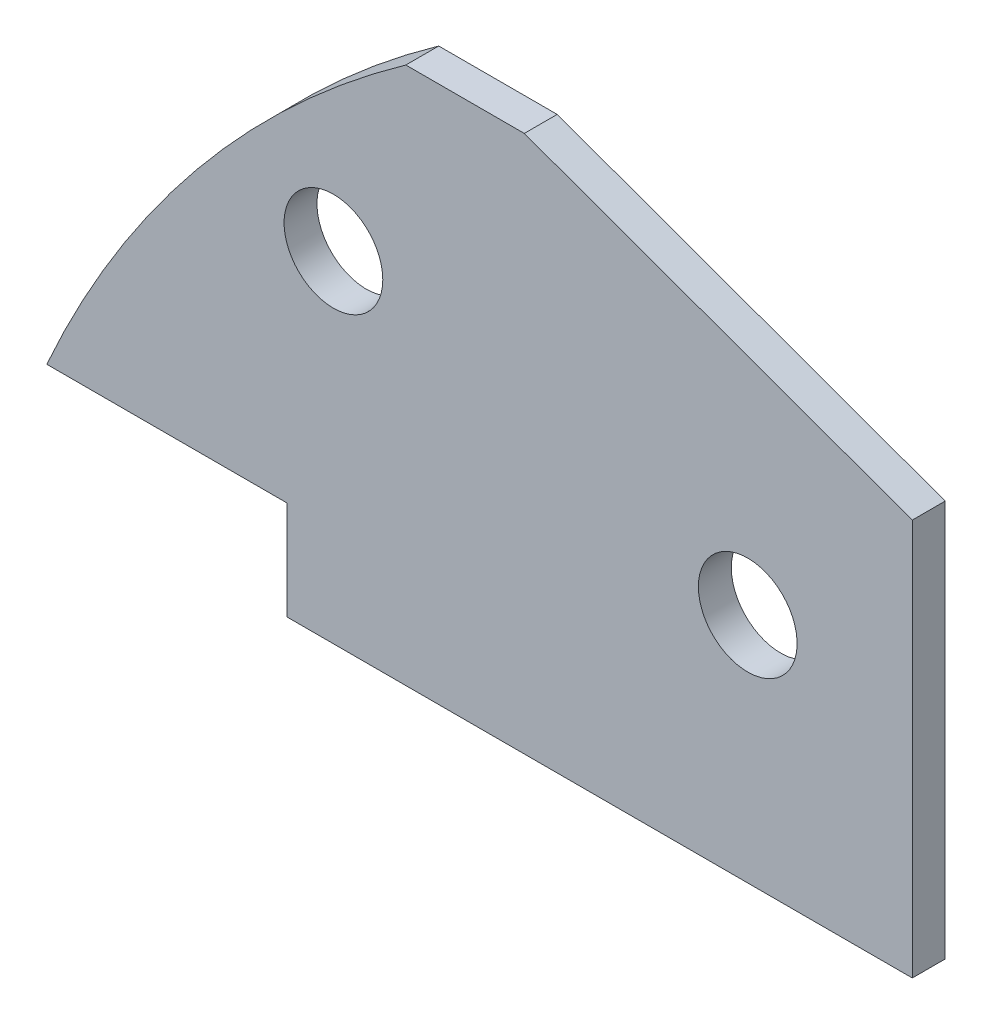
SolidWorks part; units mm, degrees
ref_plane "Front Plane" through (0, 0, 0) normal (0, 0, 1) x (1, 0, 0)
ref_plane "Top Plane" through (0, 0, 0) normal (0, 1, 0) x (1, 0, 0)
ref_plane "Right Plane" through (0, 0, 0) normal (1, 0, 0) x (0, 0, -1)
sketch "Sketch1" plane through (0, 0, 0) normal (0, 0, 1) x (1, 0, 0)
  line L2 (11, 25.5) -> (-11, 25.5)
  line L3 (-11, 25.5) -> (-22.79, 29.7803)
  line L4 (11, 25.5) -> (22.79, 29.7803)
  arc A0 (-22.79, 29.7803) -> (22.79, 29.7803) centre (0, 0) ccw
  arc A1 (-22.79, 29.7803) -> (22.79, 29.7803) centre (0, 0) ccw
  dimension "D2" = 37.5
extrude "Boss-Extrude1" add sketch "Sketch1" along normal blind 3 contours L3 A0 L4 L2
sketch "Sketch2" plane through (0, 0, 3) normal (0, 0, 1) x (1, 0, 0)
  line L0 (0, 0) -> (-25.8, 0) construction
  line L2 (0, 0) -> (0, 15.281) construction
  circle A4 centre (-25.4, 10.4969) radius 1.5
  circle A5 centre (-25.4, -10.4931) radius 1.5
  circle A6 centre (25.4, -10.4931) radius 1.5
  circle A7 centre (25.4, 10.4969) radius 1.5
  point P6 (-25.8, 0)
  dimension "D1" = 25.8
  dimension "D2" = 20.99
extrude "Cut-Extrude3" cut sketch "Sketch2" against normal blind 3
sketch "Sketch3" plane through (0, 0, 3) normal (0, 0, 1) x (1, 0, 0)
  line L1 (-30.76, 21.4493) -> (-30.76, -21.4493)
  line L3 (30.76, 21.4493) -> (30.76, -21.4493)
  arc A0 (-22.79, 29.7803) -> (22.79, 29.7803) centre (0, 0) ccw construction
  arc A1 (-30.76, 21.4493) -> (-30.76, -21.4493) centre (0, 0) ccw
  arc A2 (30.76, 21.4493) -> (30.76, -21.4493) centre (0, 0) cw
  point P10 (-30.76, 0)
extrude "Cut-Extrude4" cut sketch "Sketch3" against normal blind 10
sketch "Sketch4" plane through (0, 0, 3) normal (0, 0, 1) x (1, 0, 0)
  line L0 (-30.76, 21.4493) -> (-30.76, 16.4493) construction
  line L1 (-30.76, -21.4493) -> (-30.76, 21.4493) construction
  line L2 (30.76, 21.4493) -> (30.76, 16.4493) construction
  line L3 (30.76, 21.4493) -> (30.76, -21.4493) construction
  line L4 (-30.76, -21.4493) -> (-30.76, -16.4493) construction
  line L5 (30.76, -21.4493) -> (30.76, -16.4493) construction
  line L6 (-30.76, -16.4493) -> (-33.6997, -16.4493)
  line L7 (-30.76, 16.4493) -> (-33.6997, 16.4493)
  line L8 (30.76, 16.4493) -> (33.6997, 16.4493)
  line L9 (30.76, -16.4493) -> (33.6997, -16.4493)
  line L10 (30.76, -21.4493) -> (30.76, -16.4493)
  line L11 (30.76, 21.4493) -> (30.76, 16.4493)
  line L12 (-30.76, 16.4493) -> (-30.76, 21.4493)
  line L13 (-30.76, -21.4493) -> (-30.76, -16.4493)
  arc A0 (-33.6997, -16.4493) -> (33.6997, -16.4493) centre (0, 0) ccw
  arc A1 (-30.76, 21.4493) -> (-33.6997, 16.4493) centre (0, 0) ccw
  arc A2 (33.6997, 16.4493) -> (30.76, 21.4493) centre (0, 0) ccw
  line M2 (30.76, -21.4493) -> (30.76, 21.4493)
  line M8 (-30.76, 21.4493) -> (-30.76, -21.4493)
  dimension "D1" = 5
  dimension "D2" = 5
extrude "Boss-Extrude2" add sketch "Sketch4" against normal blind 3 contours L6 A0 M8 | A1 L7 M8 | L8 A2 M2 | A0 L9 M2
sketch "Sketch5" plane through (0, 0, 3) normal (0, 0, 1) x (1, 0, 0)
  line L0 (-30.76, 16.4493) -> (-30.2, 16.4493) construction
  line L1 (-30.76, -16.4493) -> (-30.2, -16.4493) construction
  line L2 (0, 0) -> (0, -3.3934) construction
  line L3 (-30.2, -16.4493) -> (-30.76, -16.4493)
  line L4 (-30.2, -16.4493) -> (-30.2, 16.4493)
  line L5 (-30.2, 16.4493) -> (-30.76, 16.4493)
  line L6 (-30.76, -16.4493) -> (-30.76, 16.4493)
  line L7 (30.76, -16.4493) -> (30.2, -16.4493) construction
  line L8 (30.76, 16.4493) -> (30.2, 16.4493) construction
  line L9 (30.76, -16.4493) -> (30.76, 16.4493)
  line L10 (30.2, 16.4493) -> (30.76, 16.4493)
  line L11 (30.2, -16.4493) -> (30.2, 16.4493)
  line L12 (30.2, -16.4493) -> (30.76, -16.4493)
  dimension "D2" = 0.56
extrude "Cut-Extrude5" cut sketch "Sketch5" against normal blind 3
sketch "Sketch6" plane through (0, 0, 3) normal (0, 0, 1) x (1, 0, 0)
  line L1 (-30.2, 16.4493) -> (-30, 16.4493)
  line L2 (-30.2, 16.4493) -> (-30.2, -16.4493)
  line L3 (-30.2, -16.4493) -> (-30, -16.4493)
  line L4 (-30, 16.4493) -> (-30, -16.4493)
  line L5 (30, 16.4493) -> (30, -16.4493)
  line L6 (30.2, -16.4493) -> (30, -16.4493)
  line L7 (30.2, 16.4493) -> (30.2, -16.4493)
  line L8 (30.2, 16.4493) -> (30, 16.4493)
  dimension "D1" = 0.2
extrude "Cut-Extrude6" cut sketch "Sketch6" against normal blind 3
sketch "Sketch7" plane through (0, 0, 3) normal (0, 0, 1) x (1, 0, 0)
  line L0 (0, -37.5) -> (0, -5.6) construction
  line L1 (0, -21.55) -> (-21.15, -21.55) construction
  line L2 (-21.15, -21.55) -> (-19.15, -21.55) construction
  arc A0 (-33.6997, -16.4493) -> (33.6997, -16.4493) centre (0, 0) ccw construction
  circle A1 centre (-19.15, -21.55) radius 2
  circle A2 centre (19.15, -21.55) radius 2
  dimension "D1" = 31.9
  dimension "D2" = 21.15
  dimension "D3" = 2
extrude "Cut-Extrude8" cut sketch "Sketch7" against normal blind 3 contours A1 | A2
sketch "Sketch8" plane through (0, 0, 3) normal (0, 0, 1) x (1, 0, 0)
  line L2 (-33.6997, 16.4493) -> (-37.2997, 16.4493)
  line L3 (33.6997, 16.4493) -> (37.2997, 16.4493)
  line L4 (-22.79, 29.7803) -> (-26.39, 29.7803)
  line L5 (22.79, 29.7803) -> (26.39, 29.7803)
  line L6 (0, 0) -> (0, 7.7073) construction
  arc A0 (-37.2997, 16.4493) -> (-26.39, 29.7803) centre (-7.6125, 3.2837) cw
  arc A1 (37.2997, 16.4493) -> (26.39, 29.7803) centre (7.6125, 3.2837) ccw
  arc A7 (-33.6997, 16.4493) -> (-22.79, 29.7803) centre (0, 0) cw
  arc A8 (22.79, 29.7803) -> (33.6997, 16.4493) centre (0, 0) cw
  dimension "D4" = 3.6
extrude "Boss-Extrude3" add sketch "Sketch8" against normal blind 3
sketch "Sketch9" plane through (0, 0, 3) normal (0, 0, 1) x (1, 0, 0)
  line L0 (0, 0) -> (0, 9.4958) construction
  line L1 (0, -37.5) -> (0, -37.2) construction
  line L2 (4.7339, -37.2) -> (-4.7339, -37.2)
  arc A0 (-33.6997, -16.4493) -> (33.6997, -16.4493) centre (0, 0) ccw construction
  arc A1 (-4.7339, -37.2) -> (4.7339, -37.2) centre (0, 0) ccw
  point P15 (0, -37.2)
  dimension "D1" = 0.3
extrude "Cut-Extrude9" cut sketch "Sketch9" against normal blind 3
sketch "Sketch10" plane through (0, 0, 3) normal (0, 0, 1) x (1, 0, 0)
  line L0 (-33.6997, -16.4493) -> (-37.2997, -16.4493)
  line L1 (-33.6997, -16.4493) -> (-37.2997, -16.4493) construction
  line L2 (0, 0) -> (0, 6.5031) construction
  line L3 (33.6997, -16.4493) -> (37.2997, -16.4493)
  line L4 (-4.7339, -37.2) -> (4.7339, -37.2)
  arc A0 (-37.2997, -16.4493) -> (37.2997, -16.4493) centre (0, 6.1588) ccw
  arc A1 (-33.6997, -16.4493) -> (-4.7339, -37.2) centre (0, 0) ccw
  arc A2 (33.6997, -16.4493) -> (4.7339, -37.2) centre (0, 0) cw
extrude "Boss-Extrude5" add sketch "Sketch10" against normal blind 3
sketch "Sketch11" plane through (0, 0, 3) normal (0, 0, 1) x (1, 0, 0)
  line L0 (-30, 16.4493) -> (-30, 13.4493)
  line L1 (-30, -16.4493) -> (-30, 16.4493) construction
  line L2 (-30, 13.4493) -> (30, 13.4493)
  line L3 (30, 16.4493) -> (30, -16.4493) construction
  line L4 (30, 13.4493) -> (30, 16.4493)
  line L5 (30, 16.4493) -> (37.2997, 16.4493)
  line L6 (-30, 16.4493) -> (-37.2997, 16.4493)
  line L7 (-26.39, 29.7803) -> (-22.79, 29.7803)
  line L8 (-22.79, 29.7803) -> (-11, 25.5)
  line L9 (-11, 25.5) -> (11, 25.5)
  line L10 (11, 25.5) -> (22.79, 29.7803)
  line L11 (22.79, 29.7803) -> (26.39, 29.7803)
  arc A0 (-37.2997, 16.4493) -> (-26.39, 29.7803) centre (-7.6125, 3.2837) cw
  arc A1 (37.2997, 16.4493) -> (26.39, 29.7803) centre (7.6125, 3.2837) ccw
  dimension "D1" = 3
extrude "Cut-Extrude10" cut sketch "Sketch11" against normal blind 2
sketch "Sketch12" plane through (0, 0, 3) normal (0, 0, 1) x (1, 0, 0)
  line L0 (-30, 13.4493) -> (-30, -16.4493)
  line L1 (-30, -16.4493) -> (-37.2997, -16.4493)
  line L2 (-30, 13.4493) -> (30, 13.4493)
  line L3 (30, 13.4493) -> (30, -16.4493)
  line L4 (30, -16.4493) -> (37.2997, -16.4493)
  arc A0 (-37.2997, -16.4493) -> (37.2997, -16.4493) centre (0, 6.1588) ccw
extrude "Cut-Extrude11" cut sketch "Sketch12" against normal blind 3
sketch "Sketch13" plane through (0, 0, 1) normal (0, 0, 1) x (1, 0, 0)
  line L0 (-24.59, 29.7803) -> (-24.59, 23.7803) construction
  line L1 (-22.79, 29.7803) -> (-26.39, 29.7803) construction
  line L2 (-24.59, 23.7803) -> (-28.59, 23.7803) construction
  circle A0 centre (-28.59, 23.7803) radius 1.5
  circle A1 centre (28.59, 23.7803) radius 1.5
  dimension "D3" = 3
  dimension "D1" = 6
  dimension "D2" = 4
extrude "Cut-Extrude12" cut sketch "Sketch13" against normal blind 1
sketch "Sketch14" plane through (0, 0, 0) normal (0, 0, -1) x (-1, 0, 0)
  line L0 (11, 25.5) -> (11, 13.4493)
  line L1 (-30, 13.4493) -> (30, 13.4493) construction
  line L2 (11, 13.4493) -> (-37.9211, 13.4493)
  line L3 (-37.9211, 13.4493) -> (-37.9211, 32.1404)
  line L4 (-37.9211, 32.1404) -> (-13.4606, 32.1404)
  line L5 (-13.4606, 32.1404) -> (-11, 25.5)
  line L6 (-11, 25.5) -> (11, 25.5)
extrude "Cut-Extrude13" cut sketch "Sketch14" against normal blind 1
sketch "Sketch16" plane through (0, 0, 0) normal (0, 0, -1) x (-1, 0, 0)
  line L0 (11, 25.5) -> (16, 25.5) construction
  line L1 (16, 25.5) -> (16, 20.5) construction
  circle A0 centre (16, 20.5) radius 1.5
  dimension "D1" = 5
  dimension "D2" = 5
extrude "Cut-Extrude16" cut sketch "Sketch16" against normal blind 10
